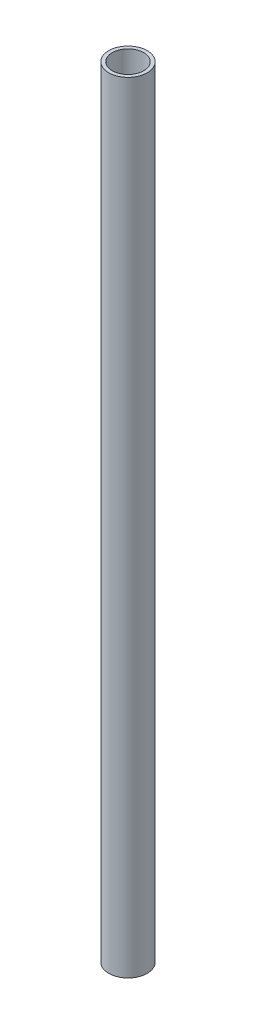
SolidWorks part; units mm, degrees
ref_plane "Front Plane" through (0, 0, 0) normal (0, 0, 1) x (1, 0, 0)
ref_plane "Top Plane" through (0, 0, 0) normal (0, 1, 0) x (1, 0, 0)
ref_plane "Right Plane" through (0, 0, 0) normal (1, 0, 0) x (0, 0, -1)
sketch "Sketch1" plane through (0, 0, 0) normal (0, 1, 0) x (1, 0, 0)
  circle A0 centre (0, 0) radius 21.082
  circle A1 centre (0, 0) radius 17.272
  dimension "D1" = 34.544
  dimension "1.66" = 42.164
extrude "Boss-Extrude1" add sketch "Sketch1" along normal blind 855.6625
ref_plane "Plane1" through (0, 0, 21.082) normal (0, 0, 1) x (1, 0, 0)
sketch "Sketch2" plane through (0, 0, 21.082) normal (0, 0, 1) x (1, 0, 0)
  line L0 (-21.082, 1.5875) -> (21.082, 1.5875) construction
  line L1 (-21.082, 855.6625) -> (-21.082, 0) construction
  line L2 (-21.082, 0) -> (21.082, 0) construction
  line L3 (-21.082, 103.1875) -> (21.082, 103.1875) construction
  line L4 (21.082, 0) -> (21.082, 855.6625) construction
  point P0 (0, 23.8125)
  point P1 (0, 61.9125)
  dimension "D1" = 1.5875
  dimension "D2" = 23.8125
  dimension "D3" = 38.1
  dimension "D4" = 101.6
hole_wizard "1/4 Clearance Hole1" positions "Sketch3" profile "Sketch4" hole size "1/4" standard "ANSI Inch"
sketch "Sketch3" plane through (0, 0, 21.082) normal (0, 0, 1) x (1, 0, 0)
  point P0 (0, 23.8125)
  point P3 (0, 61.9125)
sketch "Sketch4" plane through (0, 23.8125, 21.082) normal (1, 0, 0) x (0, -1, 0)
  line L0 (0, 0) -> (0, 42.164)
  line L1 (0, 42.164) -> (3.3782, 42.164)
  line L2 (3.3782, 42.164) -> (3.3782, 0)
  line L5 (3.3782, 0) -> (0, 0)
  line L11 (0, -6.35) -> (0, 107.95) construction
  dimension "Thru Hole Dia." = 6.7564
  dimension "Thru Hole Depth" = 42.164
